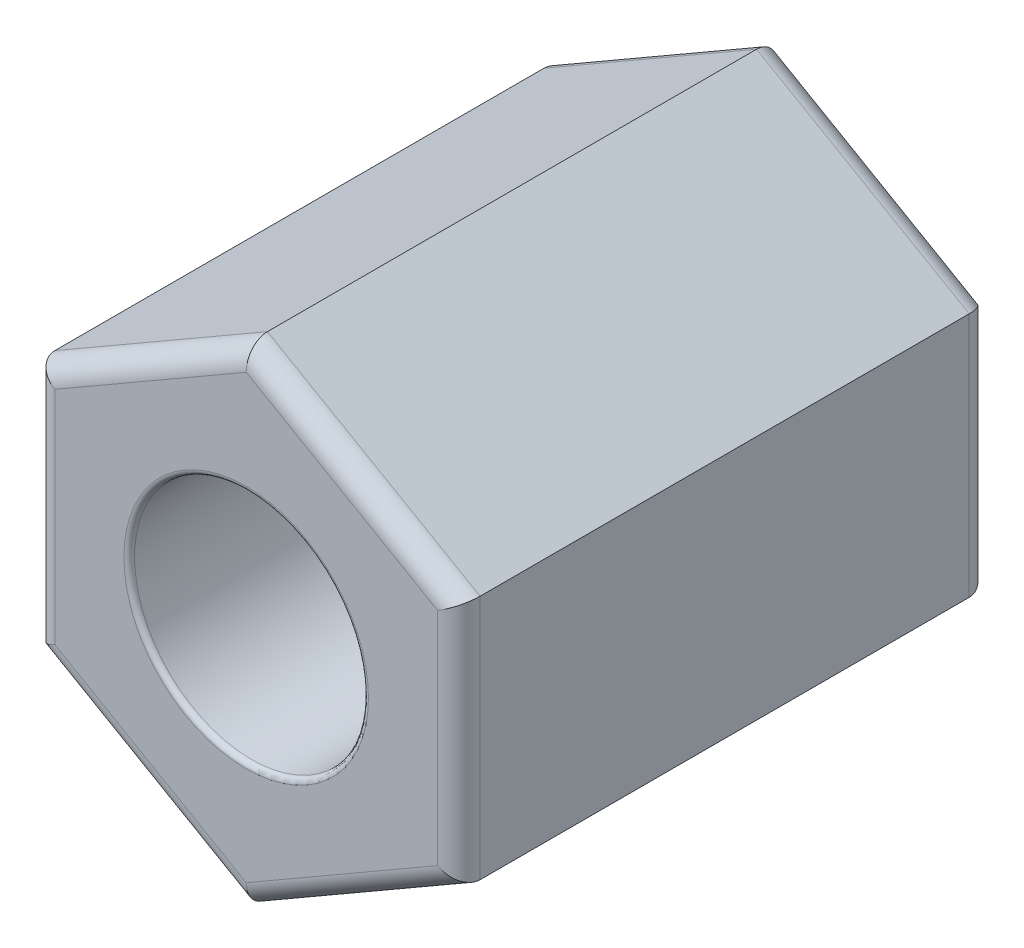
SolidWorks part; units mm, degrees
ref_plane "前视基准面" through (0, 0, 0) normal (0, 0, 1) x (1, 0, 0)
ref_plane "上视基准面" through (0, 0, 0) normal (0, 1, 0) x (1, 0, 0)
ref_plane "右视基准面" through (0, 0, 0) normal (1, 0, 0) x (0, 0, -1)
sketch "草图1" plane through (0, 0, 0) normal (0, 0, 1) x (1, 0, 0)
  line L1 (0, -23.094) -> (20, -11.547)
  line L2 (20, -11.547) -> (20, 11.547)
  line L3 (20, 11.547) -> (0, 23.094)
  line L4 (0, 23.094) -> (-20, 11.547)
  line L5 (-20, 11.547) -> (-20, -11.547)
  line L6 (-20, -11.547) -> (0, -23.094)
  circle A0 centre (0, 0) radius 20 construction
  circle A1 centre (0, 0) radius 11
  dimension "D1" = 22
  dimension "D2" = 40
extrude "凸台-拉伸1" add sketch "草图1" along normal blind 50
fillet "圆角1" radius 2 12 edges at (10, -17.3205, 0) (-10, -17.3205, 0) (-20, 0, 0) (-10, 17.3205, 0) (10, 17.3205, 0) (20, 0, 0) (20, 0, 50) (10, -17.3205, 50) (-10, -17.3205, 50) (-20, 0, 50) (-10, 17.3205, 50) (10, 17.3205, 50)
fillet "圆角2" radius 0.5 2 edges at (11, 0, 0) (11, 0, 50)
